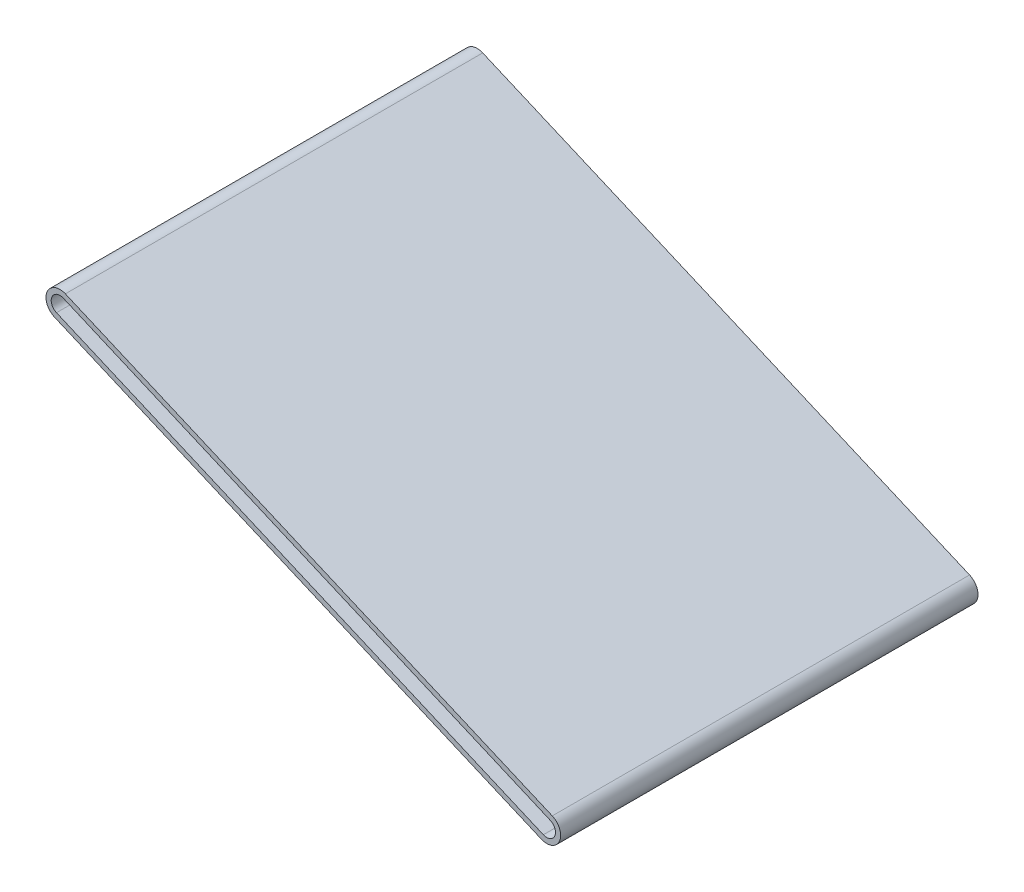
SolidWorks part; units mm, degrees
ref_plane "Front Plane" through (0, 0, 0) normal (0, 0, 1) x (1, 0, 0)
ref_plane "Top Plane" through (0, 0, 0) normal (0, 1, 0) x (1, 0, 0)
ref_plane "Right Plane" through (0, 0, 0) normal (1, 0, 0) x (0, 0, -1)
sketch "Sketch1" plane through (0, 0, 0) normal (0, 0, 1) x (1, 0, 0)
  line L0 (0, 0) -> (-355.6, 0) construction
  line L1 (-355.6, 0) -> (-355.6, 152.4) construction
  line L2 (-355.6, 152.4) -> (0, 0)
  line L3 (-347.5956, 171.077) -> (8.0044, 18.677)
  line L4 (-347.5956, 171.077) -> (-349.0964, 167.5751)
  line L5 (0, 0) -> (1.5008, 3.5019)
  line L6 (-349.0964, 167.5751) -> (6.5036, 15.1751)
  line L7 (-354.0992, 155.9019) -> (1.5008, 3.5019)
  line L8 (6.5036, 15.1751) -> (8.0044, 18.677)
  line L9 (-354.0992, 155.9019) -> (-355.6, 152.4)
  arc A0 (-355.6, 152.4) -> (-347.5956, 171.077) centre (-351.5978, 161.7385) cw
  arc A1 (0, 0) -> (8.0044, 18.677) centre (4.0022, 9.3385) ccw
  arc A2 (-349.0964, 167.5751) -> (-354.0992, 155.9019) centre (-351.5978, 161.7385) ccw
  arc A3 (1.5008, 3.5019) -> (6.5036, 15.1751) centre (4.0022, 9.3385) ccw
  dimension "D4" = 3.81
  dimension "D1" = 355.6
  dimension "D2" = 152.4
  dimension "D3" = 20.32
  dimension "D5" = 3.81
extrude "Boss-Extrude1" add sketch "Sketch1" along normal blind 304.8 contours L6 L8 L3 L4 | L7 L9 L2 L5 | A2 L4 A0 L9 | A3 L5 A1 L8
